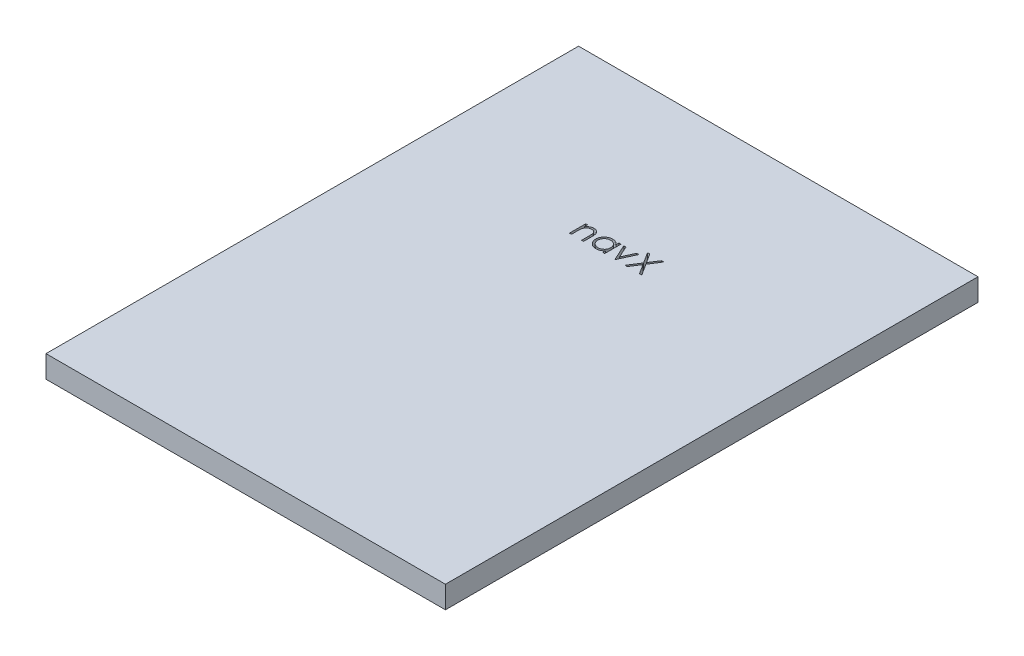
SolidWorks part; units mm, degrees
ref_plane "Front Plane" through (0, 0, 0) normal (0, 0, 1) x (1, 0, 0)
ref_plane "Top Plane" through (0, 0, 0) normal (0, 1, 0) x (1, 0, 0)
ref_plane "Right Plane" through (0, 0, 0) normal (1, 0, 0) x (0, 0, -1)
sketch "Sketch1" plane through (0, 0, 0) normal (0, 1, 0) x (1, 0, 0)
  line L1 (-28.575, 38.1) -> (28.575, 38.1)
  line L2 (-28.575, 38.1) -> (-28.575, -38.1)
  line L3 (-28.575, -38.1) -> (28.575, -38.1)
  line L4 (28.575, 38.1) -> (28.575, -38.1)
  dimension "D1" = 57.15
  dimension "D2" = 76.2
  dimension "D3" = 28.575
  dimension "D4" = 38.1
extrude "Boss-Extrude1" add sketch "Sketch1" along normal blind 3.175
sketch "Sketch2" plane through (0, 3.175, 0) normal (0, 1, 0) x (-1, 0, 0)
  line L0 (13.7267, -14.2698) -> (-11.7516, -14.2698) construction
  text T0 "navX"
extrude "Cut-Extrude1" cut sketch "Sketch2" against normal blind 1.27
